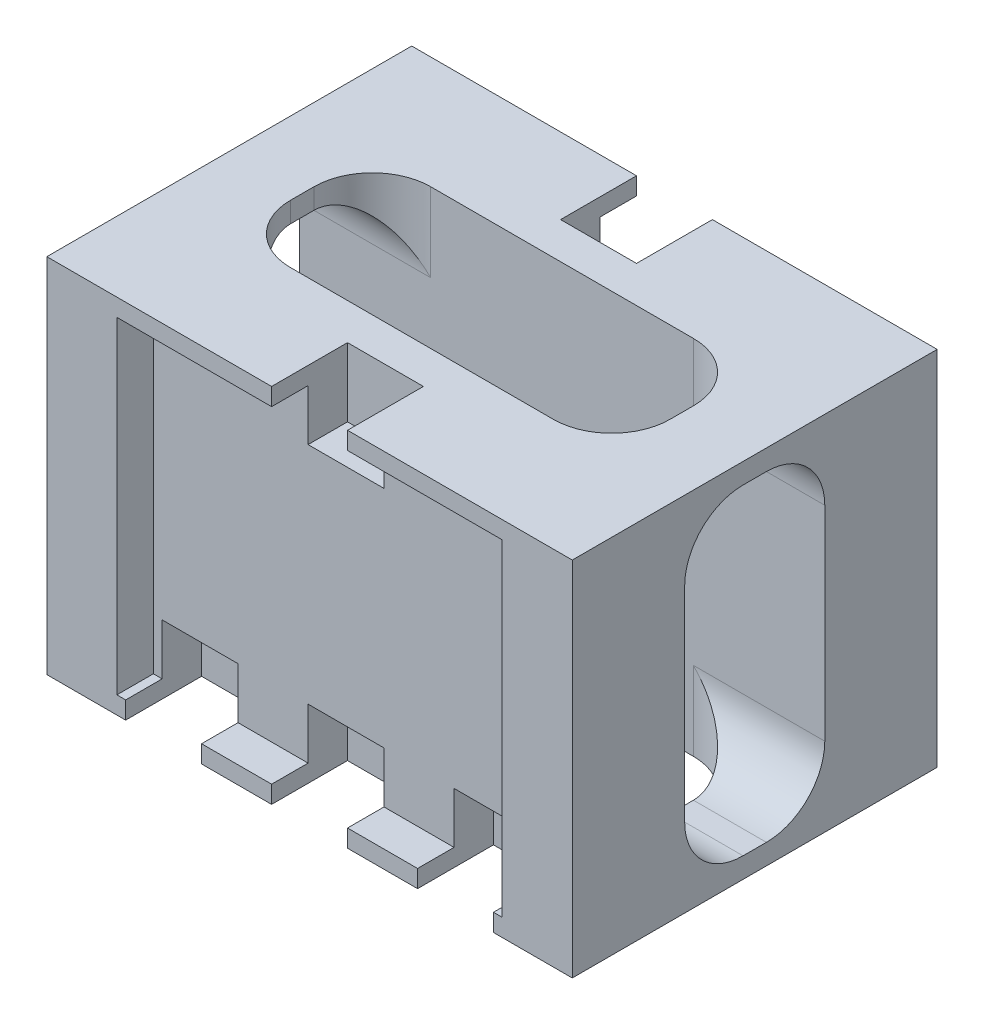
SolidWorks part; units mm, degrees
ref_plane "Front Plane" through (0, 0, 0) normal (0, 0, 1) x (1, 0, 0)
ref_plane "Top Plane" through (0, 0, 0) normal (0, 1, 0) x (1, 0, 0)
ref_plane "Right Plane" through (0, 0, 0) normal (1, 0, 0) x (0, 0, -1)
sketch "Sketch1" plane through (0, 0, 0) normal (0, 1, 0) x (1, 0, 0)
  line L1 (-22.86, -15.875) -> (22.86, -15.875)
  line L2 (-22.86, -15.875) -> (-22.86, 15.875)
  line L3 (-22.86, 15.875) -> (22.86, 15.875)
  line L4 (22.86, -15.875) -> (22.86, 15.875)
  line L5 (-22.86, -15.875) -> (22.86, 15.875) construction
  line L6 (-22.86, 15.875) -> (22.86, -15.875) construction
  point P0 (0, 0)
  dimension "D1" = 31.75
  dimension "D2" = 45.72
extrude "Boss-Extrude1" add sketch "Sketch1" along normal blind 40.64
sketch "Sketch2" plane through (0, 0, 15.875) normal (0, 0, 1) x (1, 0, 0)
  line L0 (0, 40.64) -> (0, 0) construction
  line L1 (-22.86, 40.64) -> (22.86, 40.64) construction
  line L3 (-16.764, 6.096) -> (16.764, 6.096)
  line L4 (-16.764, 6.096) -> (-16.764, 34.544)
  line L5 (-16.764, 34.544) -> (16.764, 34.544)
  line L6 (16.764, 6.096) -> (16.764, 34.544)
  line L7 (-16.764, 6.096) -> (16.764, 34.544) construction
  line L8 (-16.764, 34.544) -> (16.764, 6.096) construction
  point P5 (0, 20.32)
  point P6 (0, 20.32)
  dimension "D1" = 33.528
  dimension "D2" = 28.448
extrude "Cut-Extrude1" cut sketch "Sketch2" against normal blind 3.175
sketch "Sketch3" plane through (0, 0, 15.875) normal (0, 0, 1) x (1, 0, 0)
  line L0 (0, 34.544) -> (0, 40.64) construction
  line L1 (16.764, 34.544) -> (-16.764, 34.544) construction
  line L2 (-22.86, 40.64) -> (22.86, 40.64) construction
  line L3 (0, 6.096) -> (0, 0) construction
  line L4 (-3.302, 34.544) -> (3.302, 34.544)
  line L5 (-3.302, 34.544) -> (-3.302, 40.64)
  line L6 (-3.302, 40.64) -> (3.302, 40.64)
  line L7 (3.302, 34.544) -> (3.302, 40.64)
  line L8 (-3.302, 34.544) -> (3.302, 40.64) construction
  line L9 (-3.302, 40.64) -> (3.302, 34.544) construction
  line L10 (-16.764, 6.096) -> (16.764, 6.096) construction
  line L11 (-12.7, 0) -> (-12.7, 6.096) construction
  line L12 (-3.302, 0) -> (3.302, 0)
  line L13 (-3.302, 0) -> (-3.302, 6.096)
  line L14 (-3.302, 6.096) -> (3.302, 6.096)
  line L15 (3.302, 0) -> (3.302, 6.096)
  line L16 (-3.302, 0) -> (3.302, 6.096) construction
  line L17 (-3.302, 6.096) -> (3.302, 0) construction
  line L19 (-22.86, 0) -> (22.86, 0) construction
  line L24 (-16.764, 6.096) -> (16.764, 6.096) construction
  line L25 (12.7, 6.096) -> (12.7, 0) construction
  line L27 (-16.002, 0) -> (-9.398, 0)
  line L28 (-16.002, 0) -> (-16.002, 6.096)
  line L29 (-16.002, 6.096) -> (-9.398, 6.096)
  line L30 (-9.398, 0) -> (-9.398, 6.096)
  line L31 (-16.002, 0) -> (-9.398, 6.096) construction
  line L32 (-16.002, 6.096) -> (-9.398, 0) construction
  line L33 (9.398, 0) -> (16.002, 0)
  line L34 (9.398, 0) -> (9.398, 6.096)
  line L35 (9.398, 6.096) -> (16.002, 6.096)
  line L36 (16.002, 0) -> (16.002, 6.096)
  line L37 (9.398, 0) -> (16.002, 6.096) construction
  line L38 (9.398, 6.096) -> (16.002, 0) construction
  point P6 (0, 37.592)
  point P16 (0, 3.048)
  point P29 (-12.7, 3.048)
  point P34 (12.7, 3.048)
  dimension "D1" = 6.604
  dimension "D2" = 6.604
  dimension "D3" = 12.7
  dimension "D4" = 12.7
  dimension "D5" = 6.604
  dimension "D6" = 6.604
extrude "Cut-Extrude2" cut sketch "Sketch3" against normal blind 6.604
sketch "Sketch4" plane through (0, 0, 12.7) normal (0, 0, 1) x (1, 0, 0)
  line L0 (3.302, 34.544) -> (3.302, 40.64) construction
  line L1 (-3.302, 34.544) -> (3.302, 34.544)
  line L2 (-3.302, 34.544) -> (-3.302, 30.099)
  line L3 (-3.302, 30.099) -> (3.302, 30.099)
  line L4 (3.302, 34.544) -> (3.302, 30.099)
  line L5 (-9.398, 0) -> (-9.398, 6.096) construction
  line L6 (-16.002, 6.096) -> (-9.398, 6.096)
  line L7 (-16.002, 6.096) -> (-16.002, 10.541)
  line L8 (-16.002, 10.541) -> (-9.398, 10.541)
  line L9 (-9.398, 6.096) -> (-9.398, 10.541)
  line L10 (16.002, 0) -> (16.002, 6.096) construction
  line L11 (-3.302, 6.096) -> (3.302, 6.096)
  line L12 (-3.302, 6.096) -> (-3.302, 10.541)
  line L13 (-3.302, 10.541) -> (3.302, 10.541)
  line L14 (3.302, 6.096) -> (3.302, 10.541)
  line L15 (9.398, 6.096) -> (16.002, 6.096)
  line L16 (9.398, 6.096) -> (9.398, 10.541)
  line L17 (9.398, 10.541) -> (16.002, 10.541)
  line L18 (16.002, 6.096) -> (16.002, 10.541)
  dimension "D1" = 4.445
  dimension "D2" = 4.445
extrude "Cut-Extrude3" cut sketch "Sketch4" against normal up to surface (3.429 mm away) up to face at (-12.7, 3.048, 9.271)
mirror "Mirror1" about plane through (0, 0, 0) normal (0, 0, 1) of "Cut-Extrude3", "Cut-Extrude2", "Cut-Extrude1"
sketch "Sketch5" plane through (0, 40.64, 0) normal (0, 1, 0) x (1, 0, 0)
  line L0 (-22.86, 15.875) -> (-22.86, -15.875) construction
  line L1 (-16.51, -6.096) -> (16.51, -6.096)
  line L2 (-16.51, -6.096) -> (-16.51, 6.096)
  line L3 (-16.51, 6.096) -> (16.51, 6.096)
  line L4 (16.51, -6.096) -> (16.51, 6.096)
  line L5 (-16.51, -6.096) -> (16.51, 6.096) construction
  line L6 (-16.51, 6.096) -> (16.51, -6.096) construction
  line L7 (3.302, 9.271) -> (-3.302, 9.271) construction
  point P0 (0, 0)
  dimension "D1" = 6.35
  dimension "D2" = 3.175
extrude "Cut-Extrude4" cut sketch "Sketch5" against normal through all
sketch "Sketch6" plane through (-22.86, 0, 0) normal (-1, 0, 0) x (0, 0, 1)
  line L0 (0, 0) -> (0, 40.64) construction
  line L1 (-15.875, 40.64) -> (15.875, 40.64) construction
  line L2 (6.096, 0) -> (6.096, 40.64) construction
  line L3 (-6.096, 6.35) -> (6.096, 6.35)
  line L4 (-6.096, 6.35) -> (-6.096, 34.29)
  line L5 (-6.096, 34.29) -> (6.096, 34.29)
  line L6 (6.096, 6.35) -> (6.096, 34.29)
  line L7 (-6.096, 6.35) -> (6.096, 34.29) construction
  line L8 (-6.096, 34.29) -> (6.096, 6.35) construction
  point P5 (0, 20.32)
  dimension "D1" = 6.35
extrude "Cut-Extrude5" cut sketch "Sketch6" against normal through all
fillet "Fillet1" radius 5.08 8 edges at (-16.51, 3.175, 6.096) (-16.51, 3.175, -6.096) (16.51, 3.175, -6.096) (16.51, 3.175, 6.096) (16.51, 37.465, 6.096) (16.51, 37.465, -6.096) (-16.51, 37.465, -6.096) (-16.51, 37.465, 6.096)
fillet "Fillet2" radius 5.08 8 edges at (-17.145, 6.35, 6.096) (-17.145, 6.35, -6.096) (-17.145, 34.29, 6.096) (-17.145, 34.29, -6.096) (17.145, 34.29, 6.096) (17.145, 34.29, -6.096) (17.145, 6.35, 6.096) (17.145, 6.35, -6.096)
sketch "Sketch7" plane through (0, 40.64, 0) normal (0, 1, 0) x (1, 0, 0)
  line L1 (-22.86, 15.875) -> (22.86, 15.875)
  line L2 (-22.86, 15.875) -> (-22.86, -15.875)
  line L3 (-22.86, -15.875) -> (22.86, -15.875)
  line L4 (22.86, 15.875) -> (22.86, -15.875)
extrude "Cut-Extrude6" cut sketch "Sketch7" against normal blind 4.572
sketch "Sketch8" plane through (0, 0, 0) normal (0, -1, 0) x (1, 0, 0)
  line L1 (-22.86, 15.875) -> (22.86, 15.875)
  line L2 (-22.86, 15.875) -> (-22.86, -15.875)
  line L3 (-22.86, -15.875) -> (22.86, -15.875)
  line L4 (22.86, 15.875) -> (22.86, -15.875)
extrude "Cut-Extrude7" cut sketch "Sketch8" against normal blind 4.572
